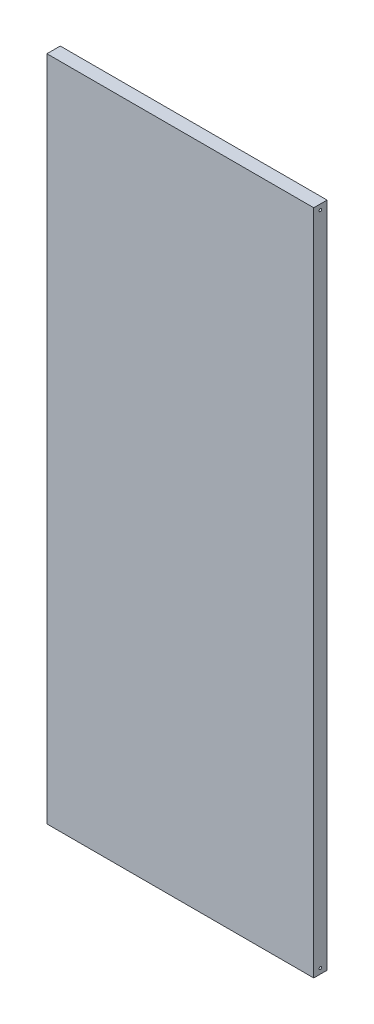
SolidWorks part; units mm, degrees
ref_plane "Front Plane" through (0, 0, 0) normal (0, 0, 1) x (1, 0, 0)
ref_plane "Top Plane" through (0, 0, 0) normal (0, 1, 0) x (1, 0, 0)
ref_plane "Right Plane" through (0, 0, 0) normal (1, 0, 0) x (0, 0, -1)
sketch "Sketch1" plane through (0, 0, 0) normal (0, 0, 1) x (1, 0, 0)
  line L1 (-23.0505, 6.2865) -> (-17.9705, 6.2865)
  line L2 (-23.0505, 6.2865) -> (-23.0505, -6.4135)
  line L3 (-23.0505, -6.4135) -> (-17.9705, -6.4135)
  line L4 (-17.9705, 6.2865) -> (-17.9705, -6.4135)
  line L5 (-23.0505, 6.2865) -> (-17.9705, -6.4135) construction
  line L6 (-23.0505, -6.4135) -> (-17.9705, 6.2865) construction
  point P0 (-20.5105, -0.0635)
  dimension "D1" = 12.7
  dimension "D2" = 5.08
extrude "Boss-Extrude1" add sketch "Sketch1" along normal blind 0.254
sketch "Sketch2" plane through (-17.9705, 0, 0) normal (1, 0, 0) x (0, 0, -1)
  line L0 (-0.127, 6.2865) -> (-0.127, 6.1849) construction
  line L1 (-0.254, 6.2865) -> (0, 6.2865) construction
  line L2 (-0.254, -6.4135) -> (0, -6.4135) construction
  circle A0 centre (-0.127, 6.1849) radius 0.0254
  circle A1 centre (-0.127, -6.3119) radius 0.0254
  dimension "D1" = 0.0508
  dimension "D3" = 0.0508
  dimension "D2" = 0.1016
  dimension "D4" = 0.1016
extrude "Cut-Extrude1" cut sketch "Sketch2" against normal through all
sketch "Sketch3" plane through (0, 0, 0) normal (0, 0, -1) x (-1, 0, 0)
  line L0 (20.5105, 6.2865) -> (20.5105, 5.4516)
  line L1 (17.9705, 6.2865) -> (23.0505, 6.2865) construction
ref_plane "Plane1" through (-20.5105, 0, 0) normal (-1, 0, 0) x (0, -1, 0)
